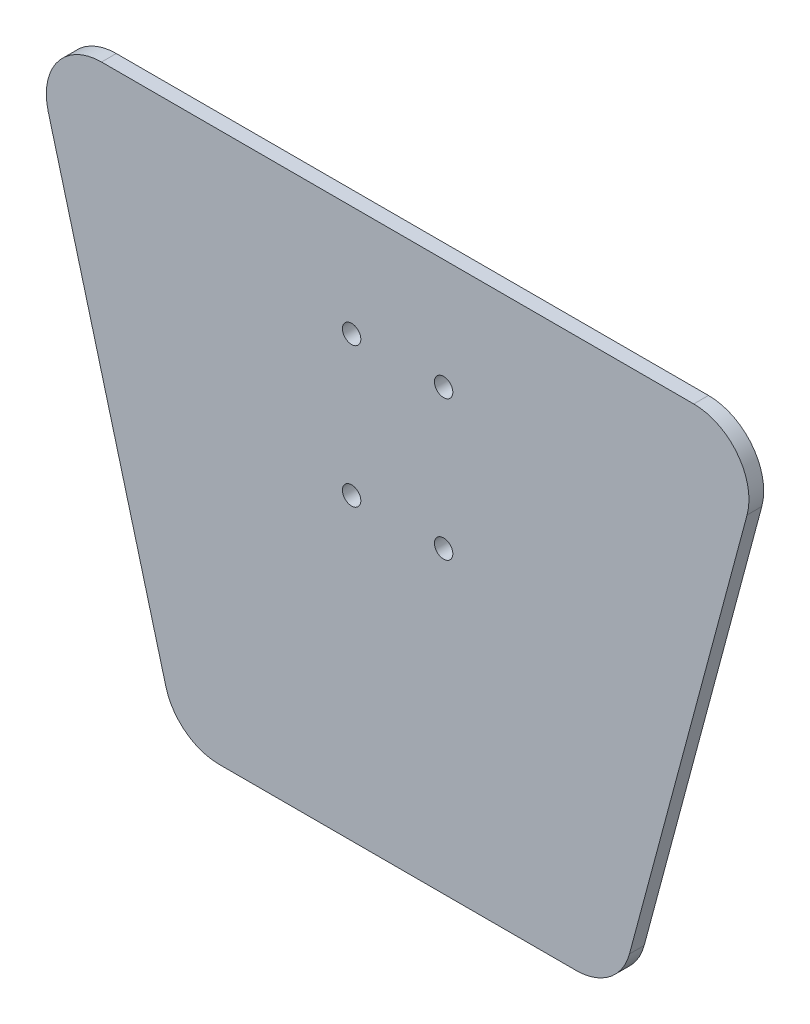
SolidWorks part; units mm, degrees
ref_plane "前视基准面" through (0, 0, 0) normal (0, 0, 1) x (1, 0, 0)
ref_plane "上视基准面" through (0, 0, 0) normal (0, 1, 0) x (1, 0, 0)
ref_plane "右视基准面" through (0, 0, 0) normal (1, 0, 0) x (0, 0, -1)
sketch "草图1" plane through (0, 0, 0) normal (0, 0, 1) x (1, 0, 0)
  line L0 (-11.5099, 0) -> (-108.4901, 0)
  line L1 (-122.979, 11.1177) -> (-154.9405, 130.3997)
  line L2 (-140.4516, 149.282) -> (20.4516, 149.282)
  line L3 (34.9405, 130.3997) -> (2.979, 11.1177)
  line L4 (-60, 0) -> (-60, 266.1022) construction
  arc A0 (-108.4901, 0) -> (-122.979, 11.1177) centre (-108.4901, 15) cw
  arc A1 (-11.5099, 0) -> (2.979, 11.1177) centre (-11.5099, 15) ccw
  arc A2 (20.4516, 149.282) -> (34.9405, 130.3997) centre (20.4516, 134.282) cw
  arc A3 (-154.9405, 130.3997) -> (-140.4516, 149.282) centre (-140.4516, 134.282) cw
  circle A4 centre (-72.5, 81.282) radius 2.5
  circle A5 centre (-72.5, 119.282) radius 2.5
  circle A6 centre (-47.5, 81.282) radius 2.5
  circle A7 centre (-47.5, 119.282) radius 2.5
  point P7 (-120, 0)
  point P10 (0, 0)
  point P13 (40, 149.282)
  point P16 (-160, 149.282)
  dimension "D5" = 15
  dimension "D6" = 5
  dimension "D7" = 5
  dimension "D1" = 120
  dimension "D2" = 200
  dimension "D3" = 105
  dimension "D4" = 105
  dimension "D8" = 38
  dimension "D9" = 12.5
  dimension "D10" = 30
extrude "凸台-拉伸1" add sketch "草图1" along normal blind 4
